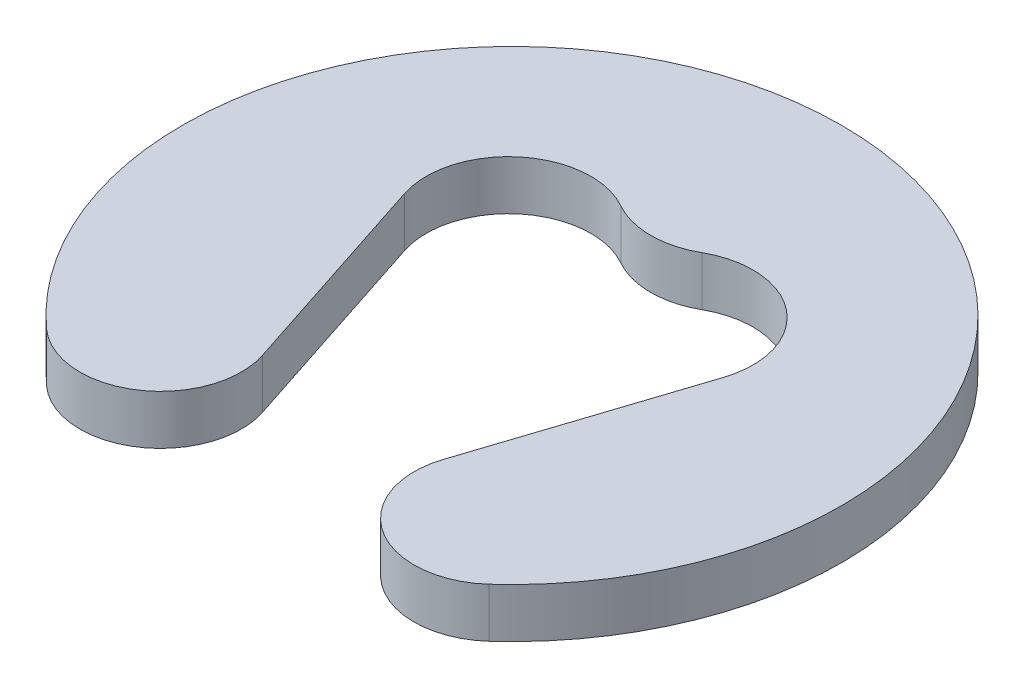
SolidWorks part; units mm, degrees
material "Plain Carbon Steel"
ref_plane "Front Plane" through (0, 0, 0) normal (0, 0, 1) x (1, 0, 0)
ref_plane "Top Plane" through (0, 0, 0) normal (0, 1, 0) x (1, 0, 0)
ref_plane "Right Plane" through (0, 0, 0) normal (1, 0, 0) x (0, 0, -1)
sketch "Sketch1" plane through (0, 0, 0) normal (0, 1, 0) x (1, 0, 0)
  circle A0 centre (0, 0) radius 2
  dimension "D1" = 4
extrude "Boss-Extrude1" add sketch "Sketch1" along normal mid plane 0.3
sketch "Sketch2" plane through (0, 0.15, 0) normal (0, 1, 0) x (1, 0, 0)
  line L0 (-0.548, -0.9662) -> (-0.9671, 0.3158)
  line L1 (0, 0) -> (0, 1.3418) construction
  line L2 (0, 1.3418) -> (0, 2) construction
  line L3 (0.548, -0.9662) -> (0.9671, 0.3158)
  arc A0 (-0.246, 0.9064) -> (-0.9671, 0.3158) centre (-0.4919, 0.4711) ccw
  arc A1 (-0.246, 0.9064) -> (0.246, 0.9064) centre (0, 1.3418) ccw
  arc A2 (-1.3432, -1.4818) -> (-0.548, -0.9662) centre (-1.014, -1.1186) ccw
  circle A3 centre (0, 0) radius 2 construction
  arc A4 (0, 2) -> (1.3432, -1.4818) centre (0, 0) ccw
  arc A5 (0.246, 0.9064) -> (0.9671, 0.3158) centre (0.4919, 0.4711) cw
  arc A6 (1.3432, -1.4818) -> (0.548, -0.9662) centre (1.014, -1.1186) cw
  circle M1 centre (0, 0) radius 2
  dimension "D1" = 1
extrude "Cut-Extrude1" cut sketch "Sketch2" against normal blind 0.3 contours A6 L3 A5 A1 A0 L0 A2 M1
